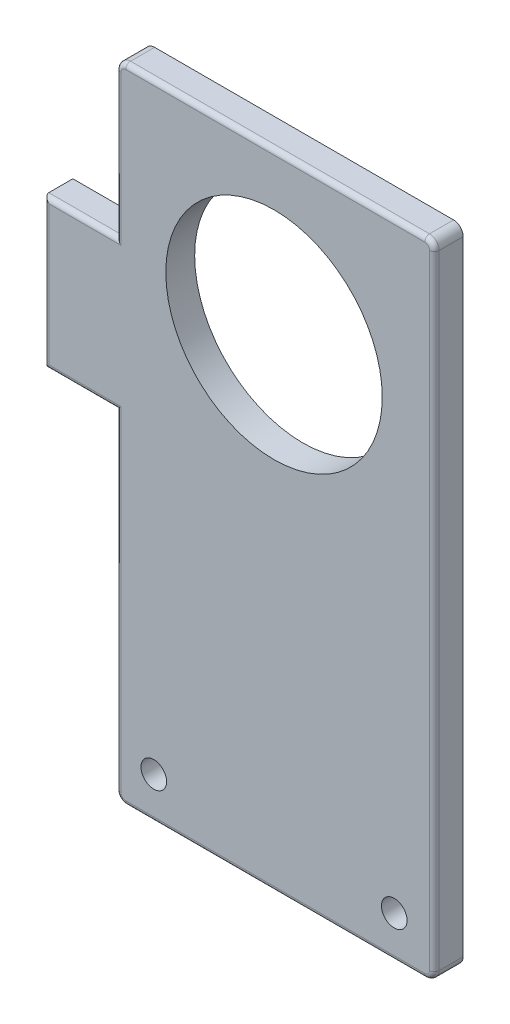
SolidWorks part; units mm, degrees
ref_plane "前视基准面" through (0, 0, 0) normal (0, 0, 1) x (1, 0, 0)
ref_plane "上视基准面" through (0, 0, 0) normal (0, 1, 0) x (1, 0, 0)
ref_plane "右视基准面" through (0, 0, 0) normal (1, 0, 0) x (0, 0, -1)
sketch "草图1" plane through (0, 0, 0) normal (0, 0, 1) x (1, 0, 0)
  line L0 (10.1, 0) -> (10.1, -21.913) construction
  line L1 (0.7, 0) -> (19.5, 0)
  line L2 (0, -0.7) -> (0, -39.6)
  line L3 (0.7, -40.3) -> (19.5, -40.3)
  line L4 (20.2, -0.7) -> (20.2, -39.6)
  arc A0 (19.5, -40.3) -> (20.2, -39.6) centre (19.5, -39.6) ccw
  arc A1 (0.7, -40.3) -> (0, -39.6) centre (0.7, -39.6) cw
  arc A2 (0.7, 0) -> (0, -0.7) centre (0.7, -0.7) ccw
  arc A3 (19.5, 0) -> (20.2, -0.7) centre (19.5, -0.7) cw
  circle A4 centre (10.1, -10.1) radius 6.75
  point P7 (20.2, -40.3)
  point P12 (0, 0)
  point P15 (20.2, 0)
  dimension "D3" = 0.7
  dimension "D4" = 13.5
  dimension "D1" = 40.3
  dimension "D2" = 20.2
  dimension "D5" = 10.1
extrude "凸台-拉伸1" add sketch "草图1" along normal blind 1.8
sketch "草图2" plane through (0, 0, 1.8) normal (0, 0, 1) x (1, 0, 0)
  line L0 (10.1, 0) -> (10.1, -23.9064) construction
  line L1 (19.5, 0) -> (0.7, 0) construction
  line L2 (20.2, -39.6) -> (20.2, -0.7) construction
  line L3 (0.7, -40.3) -> (19.5, -40.3) construction
  circle A0 centre (17.6, -2.6) radius 0.8
  circle A1 centre (17.6, -37.6) radius 0.8
  circle A2 centre (2.6, -37.6) radius 0.8
  circle A3 centre (2.6, -2.6) radius 0.8
  dimension "D1" = 2.6
  dimension "D3" = 1.6
  dimension "D4" = 2.7
  dimension "D5" = 1.6
  dimension "D2" = 2.6
extrude "切除-拉伸1" cut sketch "草图2" against normal blind 2
sketch "草图3" plane through (0, 0, 0) normal (0, 0, -1) x (-1, 0, 0)
  circle A0 centre (-17.6, -2.6) radius 1.75
  circle A1 centre (-2.6, -2.6) radius 1.75
  circle A2 centre (-17.6, -37.6) radius 1.75
  circle A3 centre (-2.6, -37.6) radius 1.75
  dimension "D1" = 3.5
  dimension "D2" = 3.5
  dimension "D3" = 3.5
  dimension "D4" = 3.5
extrude "切除-拉伸2" cut sketch "草图3" against normal blind 0.5
sketch "草图4" plane through (0, 0, 0) normal (0, 0, -1) x (-1, 0, 0)
  line L0 (0, -0.7) -> (0, -39.6) construction
  line L1 (0, -9.5) -> (4.5, -9.5)
  line L2 (0, -9.5) -> (0, -19.3)
  line L3 (0, -19.3) -> (4.5, -19.3)
  line L4 (4.5, -9.5) -> (4.5, -19.3)
  dimension "D1" = 9.5
  dimension "D2" = 9.8
  dimension "D3" = 4.5
extrude "凸台-拉伸2" add sketch "草图4" against normal up to vertex (1.8 mm away)
sketch "草图5" plane through (0, 0, 0.5) normal (0, 0, -1) x (-1, 0, 0)
  circle A0 centre (-2.6, -2.6) radius 1.75
  circle A1 centre (-17.6, -2.6) radius 1.75
extrude "凸台-拉伸3" add sketch "草图5" against normal up to vertex (1.3 mm away)
sketch "草图6" plane through (0, 0, 0) normal (0, 0, -1) x (-1, 0, 0)
  circle A0 centre (-17.6, -2.6) radius 1.75
  circle A1 centre (-2.6, -2.6) radius 1.75
extrude "凸台-拉伸4" add sketch "草图6" against normal up to vertex (1.8 mm away)
sketch "草图8" plane through (0, 0, 0) normal (0, 0, -1) x (-1, 0, 0)
  line L0 (-0.7, 0) -> (0, 0)
  line L1 (0, 0) -> (0, -0.7)
  line L2 (0, -0.7) -> (-0.7, 0)
  line L3 (-0.7, -40.3) -> (0, -40.3)
  line L4 (0, -40.3) -> (0, -39.6)
  line L5 (0, -39.6) -> (-0.7, -40.3)
  arc A0 (-0.7, -40.3) -> (0, -39.6) centre (-0.7, -39.6) ccw construction
extrude "凸台-拉伸5" add sketch "草图8" against normal up to vertex (1.8 mm away)
sketch "草图9" plane through (0, 0, 0) normal (0, 0, -1) x (-1, 0, 0)
  line L0 (0, -19.3) -> (0, -40.3) construction
  line L1 (0, -19.3) -> (4.5, -19.3) construction
  line L2 (4.5, -19.3) -> (4.5, -9.5) construction
  line L3 (4.5, -9.5) -> (0, -9.5) construction
  line L4 (0, 0) -> (0, -9.5) construction
  line L5 (0, -19.3) -> (0, -40.3)
  line L6 (0, -19.3) -> (4.5, -19.3)
  line L7 (4.5, -19.3) -> (4.5, -9.5)
  line L8 (4.5, -9.5) -> (0, -9.5)
  line L9 (0, 0) -> (0, -9.5)
  line L10 (-0.15, 0) -> (-0.15, -9.65)
  line L11 (4.35, -9.65) -> (-0.15, -9.65)
  line L12 (4.35, -19.15) -> (4.35, -9.65)
  line L13 (-0.15, -19.15) -> (4.35, -19.15)
  line L14 (-0.15, -19.15) -> (-0.15, -40.3)
  line L15 (-0.15, 0) -> (0, 0)
  line L16 (0, -40.3) -> (-0.15, -40.3)
  dimension "D1" = 0.15
extrude "切除-拉伸3" cut sketch "草图9" against normal blind 10
fillet "圆角1" radius 0.7 2 edges at (0.15, -40.3, 0.9) (0.15, 0, 0.9)
sketch "草图10" plane through (0, 0, 0) normal (0, 0, -1) x (-1, 0, 0)
  line L16 (-19.5, -40.2) -> (-0.85, -40.2)
  line L17 (-0.25, -39.6) -> (-0.25, -19.05)
  line L18 (-0.25, -19.05) -> (4.25, -19.05)
  line L19 (4.25, -19.05) -> (4.25, -9.75)
  line L20 (4.25, -9.75) -> (-0.25, -9.75)
  line L21 (-0.25, -9.75) -> (-0.25, -0.7)
  line L22 (-0.85, -0.1) -> (-19.5, -0.1)
  line L23 (-20.1, -0.7) -> (-20.1, -39.6)
  line L24 (-19.5, -40.2) -> (-0.85, -40.2)
  line L25 (-0.25, -39.6) -> (-0.25, -19.05)
  line L26 (-0.25, -19.05) -> (4.25, -19.05)
  line L27 (4.25, -19.05) -> (4.25, -9.75)
  line L28 (4.25, -9.75) -> (-0.25, -9.75)
  line L29 (-0.25, -9.75) -> (-0.25, -0.7)
  line L30 (-0.85, -0.1) -> (-19.5, -0.1)
  line L31 (-20.1, -0.7) -> (-20.1, -39.6)
  arc A8 (-0.85, -40.2) -> (-0.25, -39.6) centre (-0.85, -39.6) ccw
  arc A9 (-0.25, -0.7) -> (-0.85, -0.1) centre (-0.85, -0.7) ccw
  arc A10 (-19.5, -0.1) -> (-20.1, -0.7) centre (-19.5, -0.7) ccw
  arc A11 (-20.1, -39.6) -> (-19.5, -40.2) centre (-19.5, -39.6) ccw
  arc A12 (-0.85, -40.2) -> (-0.25, -39.6) centre (-0.85, -39.6) ccw
  arc A13 (-0.25, -0.7) -> (-0.85, -0.1) centre (-0.85, -0.7) ccw
  arc A14 (-19.5, -0.1) -> (-20.1, -0.7) centre (-19.5, -0.7) ccw
  arc A15 (-20.1, -39.6) -> (-19.5, -40.2) centre (-19.5, -39.6) ccw
  line M15 (-19.5, -40.3) -> (-0.85, -40.3)
  arc M16 (-0.85, -40.3) -> (-0.15, -39.6) centre (-0.85, -39.6) ccw
  line M17 (-0.15, -39.6) -> (-0.15, -19.15)
  line M18 (-0.15, -19.15) -> (4.35, -19.15)
  line M19 (4.35, -19.15) -> (4.35, -9.65)
  line M20 (4.35, -9.65) -> (-0.15, -9.65)
  line M21 (-0.15, -9.65) -> (-0.15, -0.7)
  arc M22 (-0.15, -0.7) -> (-0.85, 0) centre (-0.85, -0.7) ccw
  line M23 (-0.85, 0) -> (-19.5, 0)
  arc M24 (-19.5, 0) -> (-20.2, -0.7) centre (-19.5, -0.7) ccw
  line M25 (-20.2, -0.7) -> (-20.2, -39.6)
  arc M26 (-20.2, -39.6) -> (-19.5, -40.3) centre (-19.5, -39.6) ccw
  dimension "D1" = 0.1
extrude "切除-拉伸4" cut sketch "草图10" against normal blind 10 contours A15 L31 A14 L30 A13 L29 L28 L27 L26 L25 A12 L24 M26 M15 M16 M17 M18 M19 M20 M21 M22 M23 M24 M25
fillet "圆角2" radius 0.3 12 edges at (19.9243, -0.2757, 1.8) (10.175, -0.1, 1.8) (0.4257, -0.2757, 1.8) (0.25, -5.225, 1.8) (-2, -9.75, 1.8) (-4.25, -14.4, 1.8) (-2, -19.05, 1.8) (0.4257, -40.0243, 1.8) (0.25, -29.325, 1.8) (10.175, -40.2, 1.8) (19.9243, -40.0243, 1.8) (20.1, -20.15, 1.8)
